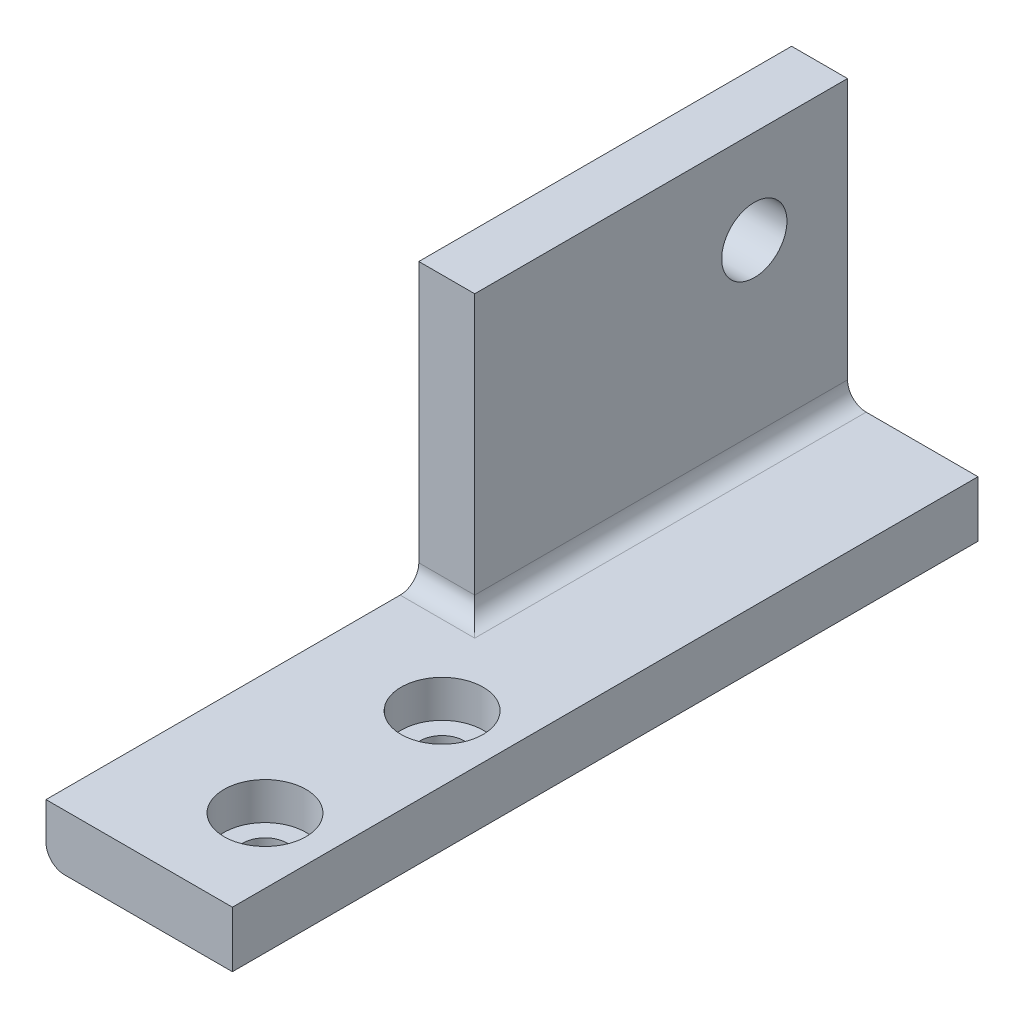
SolidWorks part; units mm, degrees
ref_plane "Front Plane" through (0, 0, 0) normal (0, 0, 1) x (1, 0, 0)
ref_plane "Top Plane" through (0, 0, 0) normal (0, 1, 0) x (1, 0, 0)
ref_plane "Right Plane" through (0, 0, 0) normal (1, 0, 0) x (0, 0, -1)
sketch "Sketch1" plane through (0, 0, 0) normal (0, 1, 0) x (1, 0, 0)
  line L0 (6.5, 5.25) -> (6.5, 14.75) construction
  line L1 (0, 0) -> (10, 0)
  line L2 (0, 0) -> (0, 20)
  line L3 (0, 20) -> (10, 20)
  line L4 (10, 0) -> (10, 20)
  circle A0 centre (6.5, 5.25) radius 1.175
  circle A1 centre (6.5, 14.75) radius 1.175
  point P9 (6.5, 10)
  point P10 (10, 10)
  dimension "D3" = 9.5
  dimension "D4" = 2.35
  dimension "D5" = 2.35
  dimension "D6" = 6.5
  dimension "D1" = 20
  dimension "D2" = 10
extrude "Boss-Extrude1" add sketch "Sketch1" along normal blind 3
sketch "Sketch2" plane through (0, 3, 0) normal (0, 1, 0) x (1, 0, 0)
  point P0 (6.5, 14.75)
  point P1 (6.5, 5.25)
hole_wizard "CBORE for M2 SHCS1" positions "Sketch2" profile "Sketch3" counterbore size "M2" standard "ANSI Metric" end condition through all
sketch "Sketch3" plane through (6.5, 3, -14.75) normal (1, 0, 0) x (0, 0, 1)
  line L0 (0, 0) -> (0, 3)
  line L1 (0, 3) -> (1.2, 3)
  line L3 (1.2, 3) -> (1.2, 2)
  line L4 (1.2, 2) -> (2.2, 2)
  line L5 (2.2, 2) -> (2.2, 0)
  line L7 (2.2, 0) -> (0, 0)
  line L11 (0, -6.35) -> (0, 107.95) construction
  dimension "Thru Hole Dia." = 2.4
  dimension "Thru Hole Depth" = 3
  dimension "C'Bore Dia." = 4.4
  dimension "C'Bore Depth" = 2
sketch "Sketch6" plane through (0, 0, -20) normal (0, 0, -1) x (-1, 0, 0)
  line L1 (0, 0) -> (-10, 0)
  line L2 (0, 0) -> (0, 3)
  line L3 (0, 3) -> (-10, 3)
  line L4 (-10, 0) -> (-10, 3)
  line L5 (-10, 3) -> (0, 3) construction
  line L6 (-10, 3) -> (-10, 0) construction
  dimension "D1" = 0
extrude "Boss-Extrude2" add sketch "Sketch6" along normal blind 20
sketch "Sketch8" plane through (0, 3, 0) normal (0, 1, 0) x (1, 0, 0)
  line L2 (0, 40) -> (3, 40)
  line L3 (0, 40) -> (0, 20)
  line L4 (0, 20) -> (3, 20)
  line L5 (3, 40) -> (3, 20)
  dimension "D1" = 3
  dimension "D2" = 20
extrude "Boss-Extrude3" add sketch "Sketch8" along normal blind 15
sketch "Sketch9" plane through (3, 0, 0) normal (1, 0, 0) x (0, 0, -1)
  line L1 (0, 3) -> (40, 3) construction
  line L2 (40, 18) -> (40, 3) construction
  circle A0 centre (35, 13) radius 1.75
  dimension "D1" = 10
  dimension "D2" = 5
extrude "Cut-Extrude1" cut sketch "Sketch9" against normal through all
fillet "Fillet1" radius 1 2 edges at (1.5, 3, -20) (3, 3, -30)
fillet "Fillet2" radius 1 1 edges at (0, 0, -20)
